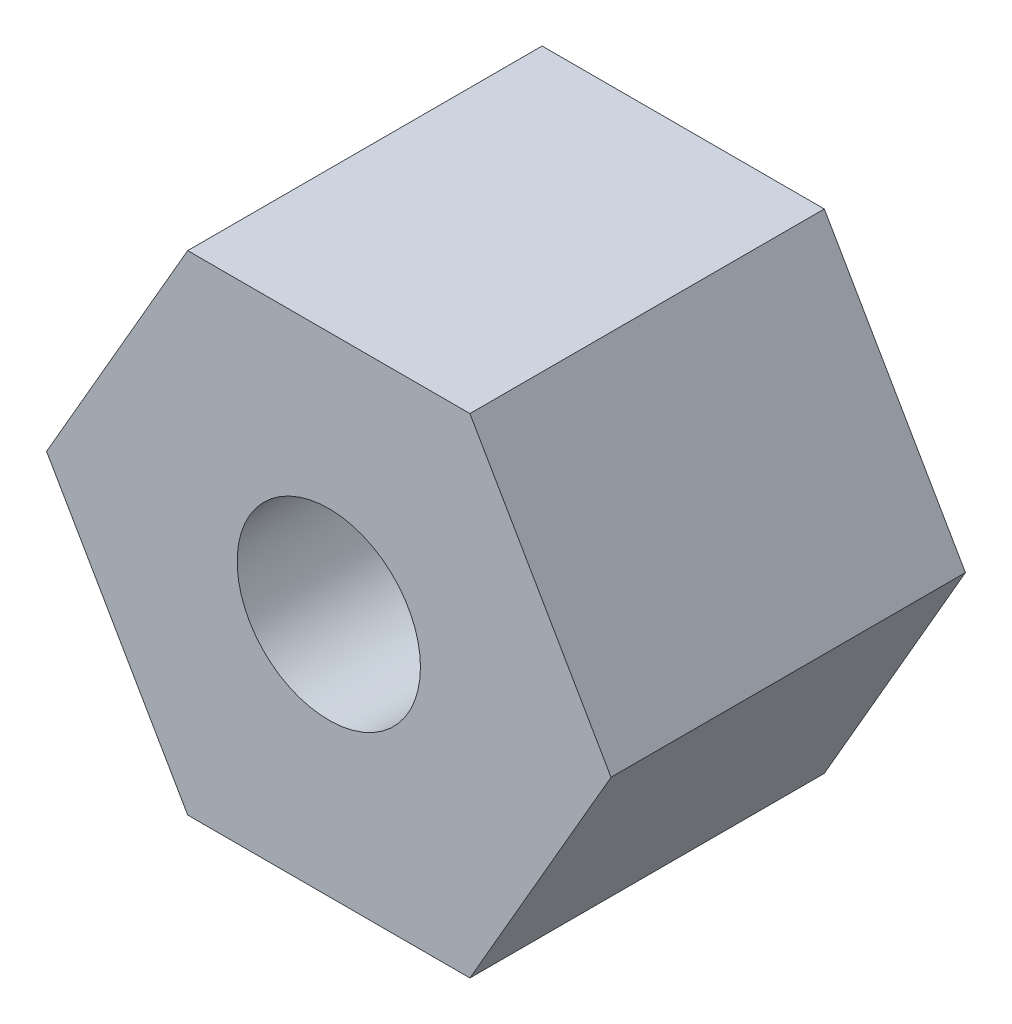
SolidWorks part; units mm, degrees
ref_plane "前视基准面" through (0, 0, 0) normal (0, 0, 1) x (1, 0, 0)
ref_plane "上视基准面" through (0, 0, 0) normal (0, 1, 0) x (1, 0, 0)
ref_plane "右视基准面" through (0, 0, 0) normal (1, 0, 0) x (0, 0, -1)
sketch "草图1" plane through (0, 0, 0) normal (0, 0, 1) x (1, 0, 0)
  line L1 (2.3094, -4) -> (4.6188, 0)
  line L2 (4.6188, 0) -> (2.3094, 4)
  line L3 (2.3094, 4) -> (-2.3094, 4)
  line L4 (-2.3094, 4) -> (-4.6188, 0)
  line L5 (-4.6188, 0) -> (-2.3094, -4)
  line L6 (-2.3094, -4) -> (2.3094, -4)
  circle A0 centre (0, 0) radius 1.5
  circle A1 centre (0, 0) radius 4 construction
  dimension "D1" = 3
  dimension "D2" = 8
extrude "凸台-拉伸1" add sketch "草图1" along normal blind 5.8
